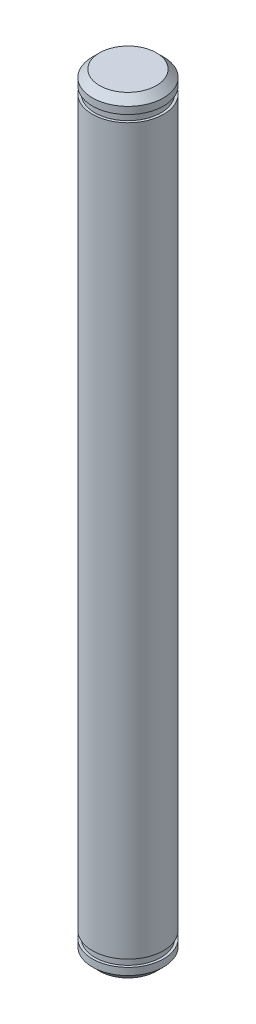
SolidWorks part; units mm, degrees
ref_plane "前视基准面" through (0, 0, 0) normal (0, 0, 1) x (1, 0, 0)
ref_plane "上视基准面" through (0, 0, 0) normal (0, 1, 0) x (1, 0, 0)
ref_plane "右视基准面" through (0, 0, 0) normal (1, 0, 0) x (0, 0, -1)
other "Configuration Table"
sketch "草图1" plane through (0, 0, 0) normal (0, 0, 1) x (1, 0, 0)
  line L0 (0, 17.9143) -> (0, -10.0949) construction
  line L1 (0, 54) -> (5, 54)
  line L2 (5, 54) -> (5, 15)
  line L4 (5, 15) -> (5, -15)
  line L6 (5, -15) -> (5, -54)
  line L7 (5, -54) -> (0, -54)
  line L8 (0, 0) -> (25.4592, 0) construction
  line L9 (0, 54) -> (0, -54)
  dimension "D1" = 5
  dimension "D3" = 30
  dimension "D4" = 39
  dimension "D5" = 39
revolve "旋转1" add sketch "草图1" angle 360 about L9
chamfer "倒角1" distance 1 angle 45 2 edges at (-5, -54, 0) (-5, 54, 0)
ref_plane "基准面1" through (0, 0, 0) normal (0, 1, 0) x (1, 0, 0)
sketch "草图2" plane through (0, 54, 0) normal (0, 1, 0) x (1, 0, 0)
  circle A0 centre (0, 0) radius 5 construction
  circle A1 centre (0, 0) radius 5
  circle A2 centre (0, 0) radius 4.65
  dimension "D1" = 9.3
extrude "切除-拉伸1" cut sketch "草图2" along normal blind 1 from offset 3 offset against normal yes
mirror "镜向1" about plane through (0, 0, 0) normal (0, 1, 0) of "切除-拉伸1"
